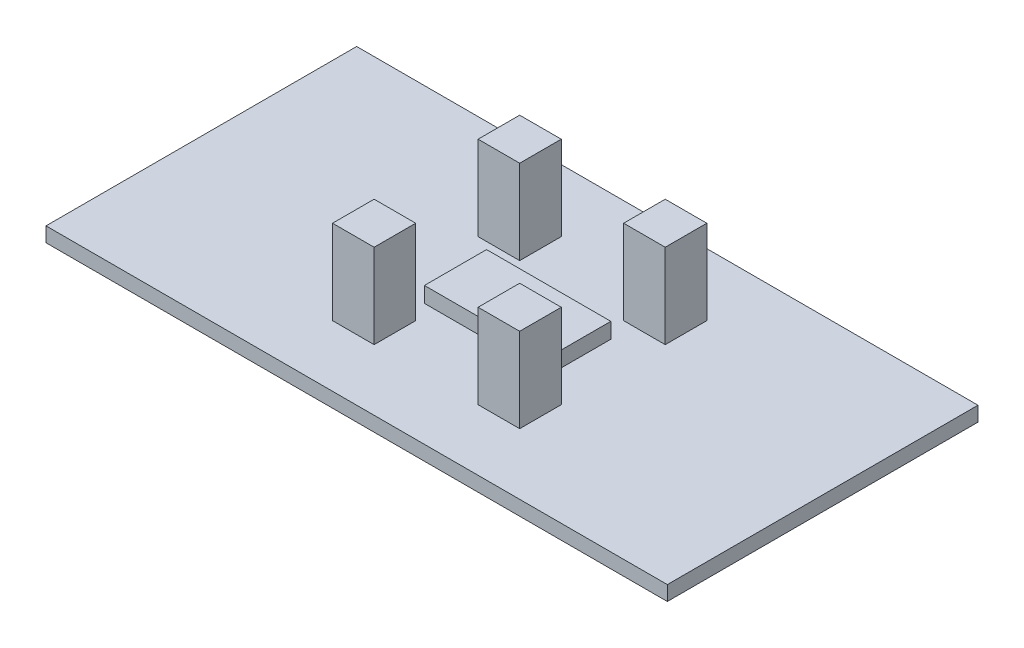
SolidWorks part; units mm, degrees
material "Pine"
ref_plane "Front" through (0, 0, 0) normal (0, 0, 1) x (1, 0, 0)
ref_plane "Top" through (0, 0, 0) normal (0, 1, 0) x (1, 0, 0)
ref_plane "Right" through (0, 0, 0) normal (1, 0, 0) x (0, 0, -1)
sketch "Sketch1" plane through (0, 0, 0) normal (0, 1, 0) x (1, 0, 0)
  line L1 (-287.8667, 131.8381) -> (220.1333, 131.8381)
  line L2 (-287.8667, 131.8381) -> (-287.8667, -122.1619)
  line L3 (-287.8667, -122.1619) -> (220.1333, -122.1619)
  line L4 (220.1333, 131.8381) -> (220.1333, -122.1619)
  dimension "D1" = 254
  dimension "D2" = 508
extrude "Boss-Extrude1" add sketch "Sketch1" along normal blind 12
sketch "Sketch2" plane through (0, 12, 0) normal (0, 1, 0) x (1, 0, 0)
  line L0 (-103.5967, 80.8381) -> (-69.5967, 80.8381)
  line L1 (15.4033, 80.8381) -> (49.4033, 80.8381)
  line L2 (15.4033, 80.8381) -> (15.4033, 46.8381)
  line L3 (15.4033, 46.8381) -> (49.4033, 46.8381)
  line L4 (49.4033, 80.8381) -> (49.4033, 46.8381)
  line L5 (-103.5967, 80.8381) -> (-103.5967, 46.8381)
  line L6 (-103.5967, 46.8381) -> (-69.5967, 46.8381)
  line L7 (-69.5967, 80.8381) -> (-69.5967, 46.8381)
  line L8 (-103.5967, -38.1619) -> (-69.5967, -38.1619)
  line L9 (-103.5967, -38.1619) -> (-103.5967, -72.1619)
  line L10 (-103.5967, -72.1619) -> (-69.5967, -72.1619)
  line L11 (-69.5967, -38.1619) -> (-69.5967, -72.1619)
  line L12 (15.4033, -38.1619) -> (49.4033, -38.1619)
  line L13 (15.4033, -38.1619) -> (15.4033, -72.1619)
  line L14 (15.4033, -72.1619) -> (49.4033, -72.1619)
  line L15 (49.4033, -38.1619) -> (49.4033, -72.1619)
  line L16 (220.1333, -122.1619) -> (220.1333, 131.8381) construction
  point P18 (15.4033, 63.8381)
  point P19 (32.4033, 46.8381)
  dimension "D2" = 34
  dimension "D3" = 204.73
  dimension "D4" = 85
  dimension "D5" = 204.73
  dimension "D6" = 85
  dimension "D7" = 0
  dimension "D8" = 34
  dimension "D9" = 34
  dimension "D10" = 34
  dimension "D11" = 0
  dimension "D12" = 85
  dimension "D13" = 34
  dimension "D14" = 34
  dimension "D16" = 34
  dimension "D17" = 34
extrude "Boss-Extrude2" add sketch "Sketch2" along normal blind 69 separate body
sketch "Sketch3" plane through (0, 12, 0) normal (0, 1, 0) x (1, 0, 0)
  line L1 (-78.2613, 28.4381) -> (23.3387, 28.4381)
  line L2 (-78.2613, 28.4381) -> (-78.2613, -22.3619)
  line L3 (-78.2613, -22.3619) -> (23.3387, -22.3619)
  line L4 (23.3387, 28.4381) -> (23.3387, -22.3619)
  line L5 (-287.8667, -122.1619) -> (220.1333, -122.1619) construction
  point P3 (-33.8667, 131.8381)
  dimension "D1" = 101.6
  dimension "D2" = 50.8
  dimension "D3" = 99.8
extrude "Boss-Extrude3" add sketch "Sketch3" along normal blind 12.7
